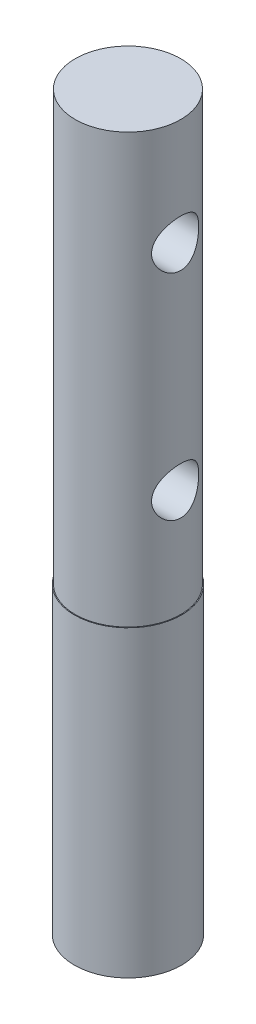
SolidWorks part; units mm, degrees
material "ASTM A36 Steel"
ref_plane "Front Plane" through (0, 0, 0) normal (0, 0, 1) x (1, 0, 0)
ref_plane "Top Plane" through (0, 0, 0) normal (0, 1, 0) x (1, 0, 0)
ref_plane "Right Plane" through (0, 0, 0) normal (1, 0, 0) x (0, 0, -1)
sketch "Sketch1" plane through (0, 0, 0) normal (0, 1, 0) x (1, 0, 0)
  circle A0 centre (0, 0) radius 25
  dimension "D1" = 50
extrude "Boss-Extrude1" add sketch "Sketch1" along normal blind 141.5
sketch "Sketch2" plane through (0, 141.5, 0) normal (0, 1, 0) x (1, 0, 0)
  circle A0 centre (0, 0) radius 24.61
  dimension "D1" = 49.22
extrude "Boss-Extrude2" add sketch "Sketch2" along normal blind 200
ref_plane "Plane1" through (25, 0, 0) normal (1, 0, 0) x (0, 0, -1)
sketch "Sketch3" plane through (0, 0, 0) normal (1, 0, 0) x (0, 0, -1)
  line L0 (25, 141.5) -> (-25, 141.5) construction
  circle A0 centre (0, 191.5) radius 11
  circle A1 centre (0, 291.5) radius 11
  dimension "D1" = 22
  dimension "D2" = 50
  dimension "D3" = 22
  dimension "D4" = 100
extrude "Cut-Extrude1" cut sketch "Sketch3" against normal through all both and the other way through all
